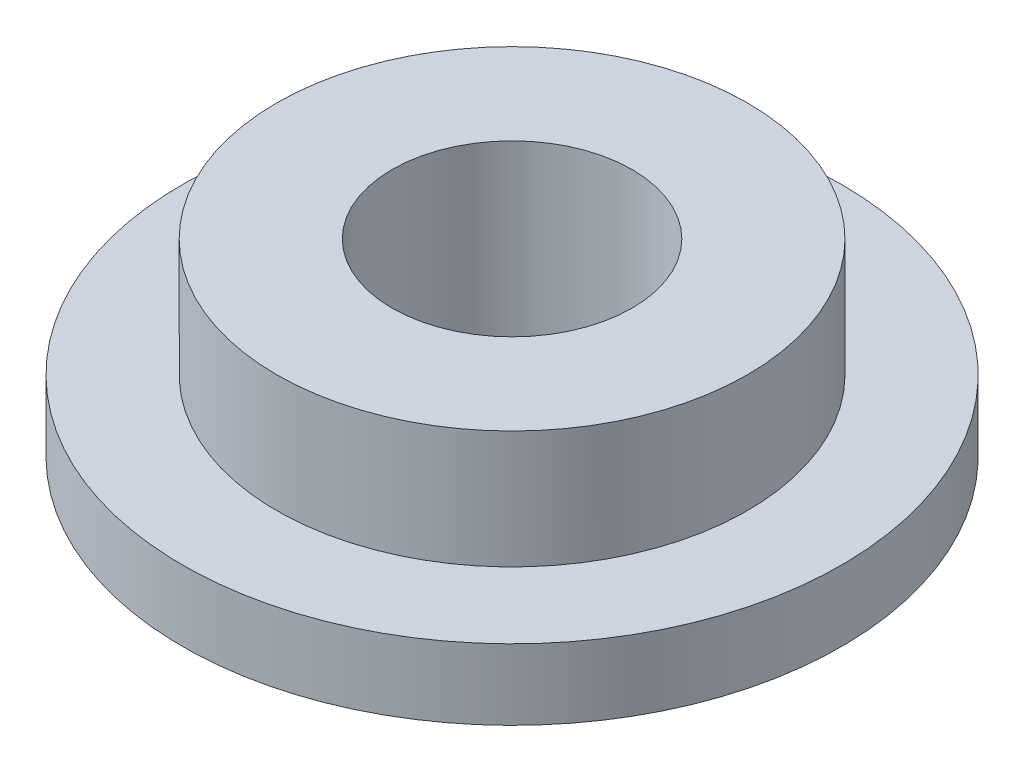
SolidWorks part; units mm, degrees
ref_plane "Front Plane" through (0, 0, 0) normal (0, 0, 1) x (1, 0, 0)
ref_plane "Top Plane" through (0, 0, 0) normal (0, 1, 0) x (1, 0, 0)
ref_plane "Right Plane" through (0, 0, 0) normal (1, 0, 0) x (0, 0, -1)
sketch "Sketch1" plane through (0, 0, 0) normal (0, 1, 0) x (1, 0, 0)
  circle A0 centre (0, 0) radius 2.55
  circle A1 centre (0, 0) radius 5
  dimension "D1" = 5.1
  dimension "D2" = 10
extrude "Boss-Extrude1" add sketch "Sketch1" along normal blind 4
sketch "Sketch2" plane through (0, 0, 0) normal (0, -1, 0) x (-1, 0, 0)
  circle A0 centre (0, 0) radius 5
  circle A1 centre (0, 0) radius 7
  dimension "D1" = 14
extrude "Boss-Extrude2" add sketch "Sketch2" against normal blind 1.5
